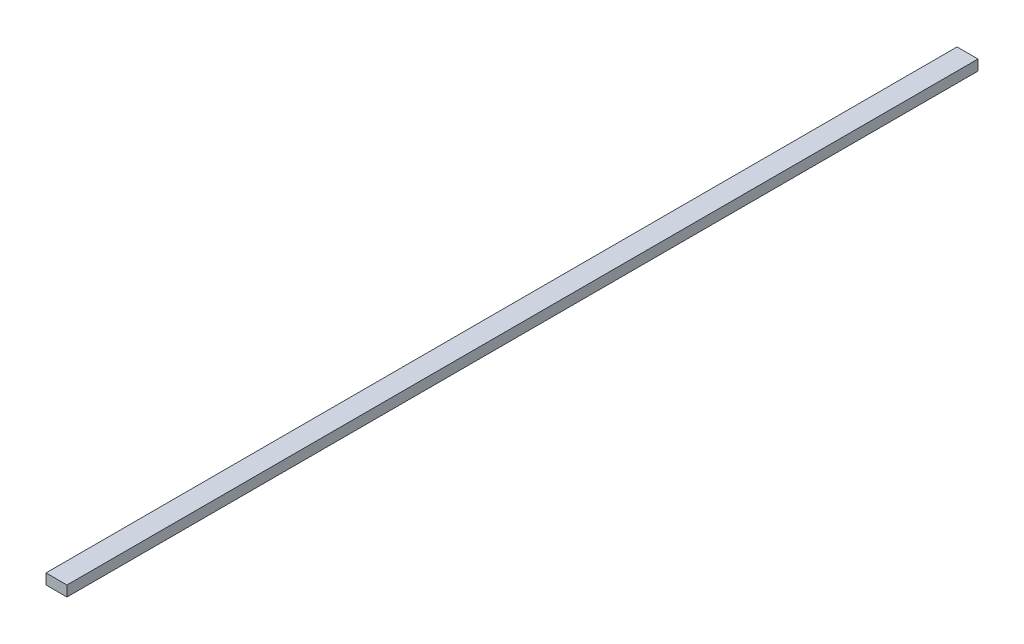
SolidWorks part; units mm, degrees
material "Pine"
ref_plane "Front Plane" through (0, 0, 0) normal (0, 0, 1) x (1, 0, 0)
ref_plane "Top Plane" through (0, 0, 0) normal (0, 1, 0) x (1, 0, 0)
ref_plane "Right Plane" through (0, 0, 0) normal (1, 0, 0) x (0, 0, -1)
sketch "Sketch1" plane through (0, 0, 0) normal (0, 1, 0) x (1, 0, 0)
  line L1 (0, 0) -> (25.4, 0)
  line L2 (0, 0) -> (0, 1104.9)
  line L3 (0, 1104.9) -> (25.4, 1104.9)
  line L4 (25.4, 0) -> (25.4, 1104.9)
  dimension "D1" = 25.4
  dimension "D2" = 1104.9
extrude "Boss-Extrude1" add sketch "Sketch1" along normal blind 12.7
